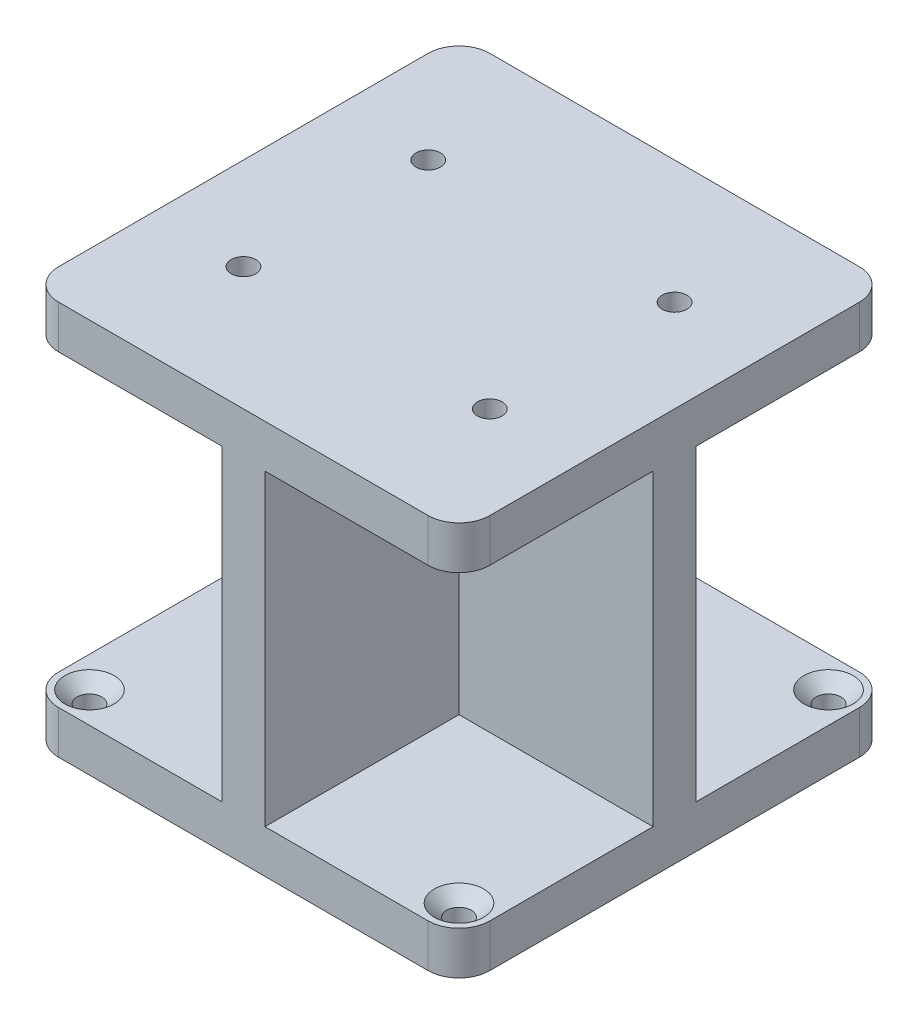
SolidWorks part; units mm, degrees
ref_plane "Front Plane" through (0, 0, 0) normal (0, 0, 1) x (1, 0, 0)
ref_plane "Top Plane" through (0, 0, 0) normal (0, 1, 0) x (1, 0, 0)
ref_plane "Right Plane" through (0, 0, 0) normal (1, 0, 0) x (0, 0, -1)
sketch "Sketch1" plane through (0, 0, 0) normal (0, 1, 0) x (1, 0, 0)
  line L0 (0, 20) -> (0, -16.1207) construction
  line L1 (-30, 35) -> (30, 35)
  line L2 (-35, 30) -> (-35, -30)
  line L3 (-30, -35) -> (30, -35)
  line L4 (35, 30) -> (35, -30)
  line L5 (-35, 35) -> (35, -35) construction
  line L6 (-35, -35) -> (35, 35) construction
  line L7 (-18.374, 0) -> (20, 0) construction
  arc A0 (30, 35) -> (35, 30) centre (30, 30) cw
  arc A1 (35, -30) -> (30, -35) centre (30, -30) cw
  arc A2 (-35, -30) -> (-30, -35) centre (-30, -30) ccw
  arc A3 (-35, 30) -> (-30, 35) centre (-30, 30) cw
  circle A4 centre (30, 30) radius 2
  circle A5 centre (-30, 30) radius 2
  circle A6 centre (30, -30) radius 2
  circle A7 centre (-30, -30) radius 2
  point P0 (0, 0)
  dimension "D2" = 5
  dimension "D3" = 4
  dimension "D1" = 70
extrude "Boss-Extrude1" add sketch "Sketch1" along normal mid plane 7
sketch "Sketch2" plane through (0, 3.5, 0) normal (0, 1, 0) x (1, 0, 0)
  line L0 (-3.5, 3.5) -> (-0.35, 3.5) construction
  line L1 (-3.5, 35) -> (3.5, 35)
  line L2 (-3.5, 35) -> (-3.5, 3.5)
  line L3 (-3.5, -35) -> (3.5, -35)
  line L4 (3.5, 35) -> (3.5, 3.5)
  line L5 (-3.5, 35) -> (3.5, -35) construction
  line L6 (-3.5, -35) -> (3.5, 35) construction
  line L7 (-35, 3.5) -> (-3.5, 3.5)
  line L8 (-35, 3.5) -> (-35, -3.5)
  line L9 (-35, -3.5) -> (-3.5, -3.5)
  line L10 (35, 3.5) -> (35, -3.5)
  line L11 (-35, 3.5) -> (35, -3.5) construction
  line L12 (-35, -3.5) -> (35, 3.5) construction
  line L13 (-0.35, 3.5) -> (0.35, 3.5) construction
  line L14 (-3.5, 3.5) -> (-3.5, 0.35) construction
  line L15 (-3.5, 0.35) -> (-3.5, -0.35) construction
  line L16 (-3.5, -0.35) -> (-3.5, -3.5) construction
  line L17 (-3.5, -3.5) -> (-3.5, -35)
  line L18 (-3.5, -3.5) -> (-0.35, -3.5) construction
  line L19 (-0.35, -3.5) -> (0.35, -3.5) construction
  line L20 (0.35, -3.5) -> (3.5, -3.5) construction
  line L21 (3.5, -3.5) -> (35, -3.5)
  line L22 (3.5, -0.35) -> (3.5, -3.5) construction
  line L23 (3.5, -3.5) -> (3.5, -35)
  line L24 (0.35, 3.5) -> (3.5, 3.5) construction
  line L25 (3.5, 3.5) -> (35, 3.5)
  line L26 (3.5, 3.5) -> (3.5, 0.35) construction
  line L27 (3.5, 0.35) -> (3.5, -0.35) construction
  line L28 (30, 35) -> (-30, 35) construction
  point P0 (0, 0)
  point P5 (0, 0)
  dimension "D1" = 7
  dimension "D2" = 7
  dimension "D3" = 70
extrude "Boss-Extrude2" add sketch "Sketch2" along normal blind 50
sketch "Sketch3" plane through (0, 53.5, 0) normal (0, 1, 0) x (1, 0, 0)
  line L0 (0, 36.6469) -> (0, -37.9185) construction
  line L1 (30, -35) -> (-30, -35)
  line L2 (35, -30) -> (35, 30)
  line L3 (30, 35) -> (-30, 35)
  line L4 (-35, -30) -> (-35, 30)
  line L5 (35, -35) -> (-35, 35) construction
  line L6 (35, 35) -> (-35, -35) construction
  line L7 (-40.659, 0) -> (48.9233, 0) construction
  line L8 (20, 30) -> (20, -24.477) construction
  arc A0 (30, 35) -> (35, 30) centre (30, 30) cw
  arc A1 (35, -30) -> (30, -35) centre (30, -30) cw
  arc A2 (-30, -35) -> (-35, -30) centre (-30, -30) cw
  arc A3 (-30, 35) -> (-35, 30) centre (-30, 30) ccw
  circle A8 centre (20, -15) radius 2
  circle A9 centre (20, 15) radius 2
  circle A10 centre (-20, 15) radius 2
  circle A11 centre (-20, -15) radius 2
  point P0 (0, 0)
  dimension "D2" = 5
  dimension "D3" = 15
  dimension "D4" = 30
  dimension "D5" = 4
  dimension "D1" = 70
extrude "Boss-Extrude3" add sketch "Sketch3" along normal blind 7
chamfer "Chamfer1" distance 2 angle 45 4 edges at (30, 3.5, 28) (-30, 3.5, 32) (30, 3.5, -28) (-30, 3.5, -32)
